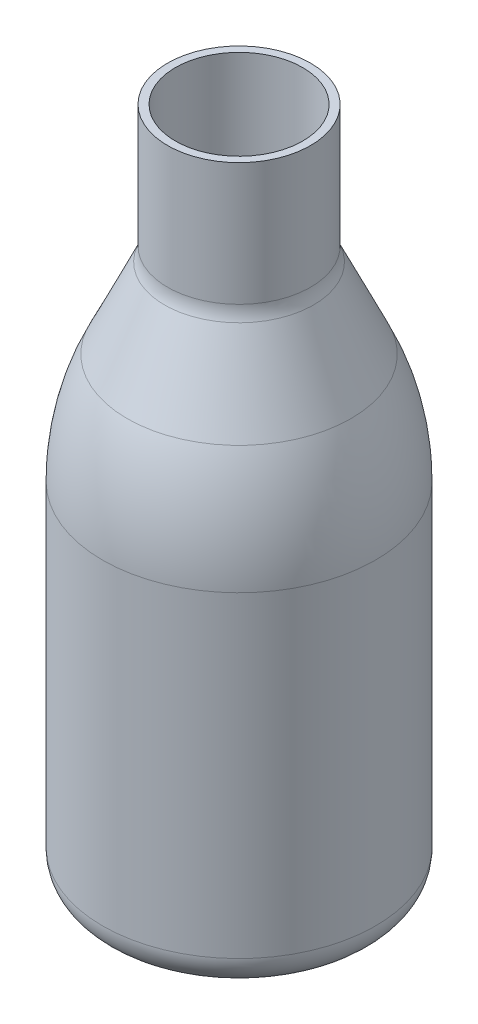
SolidWorks part; units mm, degrees
ref_plane "Front" through (0, 0, 0) normal (0, 0, 1) x (1, 0, 0)
ref_plane "Top" through (0, 0, 0) normal (0, 1, 0) x (1, 0, 0)
ref_plane "Right" through (0, 0, 0) normal (1, 0, 0) x (0, 0, -1)
sketch "Sketch1" plane through (0, 0, 0) normal (0, 0, 1) x (1, 0, 0)
  line L0 (0, 0) -> (0, 132.08)
  line L1 (0, 0) -> (-26.67, 0)
  line L2 (-26.67, 0) -> (-26.67, 79.5745)
  line L3 (-26.67, 79.5745) -> (-13.97, 106.68)
  line L4 (-13.97, 106.68) -> (-13.97, 132.08)
  line L5 (-13.97, 132.08) -> (0, 132.08)
  dimension "D1" = 26.67
  dimension "D2" = 132.08
  dimension "D3" = 25.4
  dimension "D4" = 13.97
  dimension "D5" = 79.5745
revolve "Revolve1" add sketch "Sketch1" angle 360 about L0
fillet "Fillet1" radius 6.35 2 edges at (0, 0, -26.67) (0, 106.68, -13.97)
fillet "Fillet2" radius 50.8 1 edges at (0, 79.5745, -26.67)
shell "Shell1" thickness 1.524
